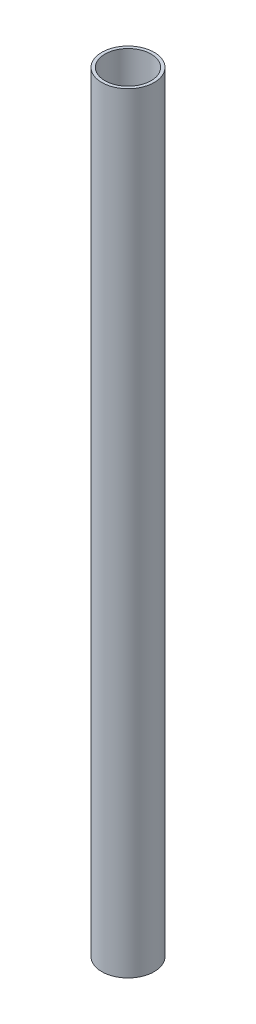
SolidWorks part; units mm, degrees
ref_plane "Front Plane" through (0, 0, 0) normal (0, 0, 1) x (1, 0, 0)
ref_plane "Top Plane" through (0, 0, 0) normal (0, 1, 0) x (1, 0, 0)
ref_plane "Right Plane" through (0, 0, 0) normal (1, 0, 0) x (0, 0, -1)
sketch "Sketch1" plane through (0, 0, 0) normal (0, 1, 0) x (1, 0, 0)
  circle A0 centre (0, 0) radius 15
  circle A1 centre (0, 0) radius 17
  dimension "D1" = 2
  dimension "D2" = 30
extrude "Boss-Extrude1" add sketch "Sketch1" along normal blind 500
